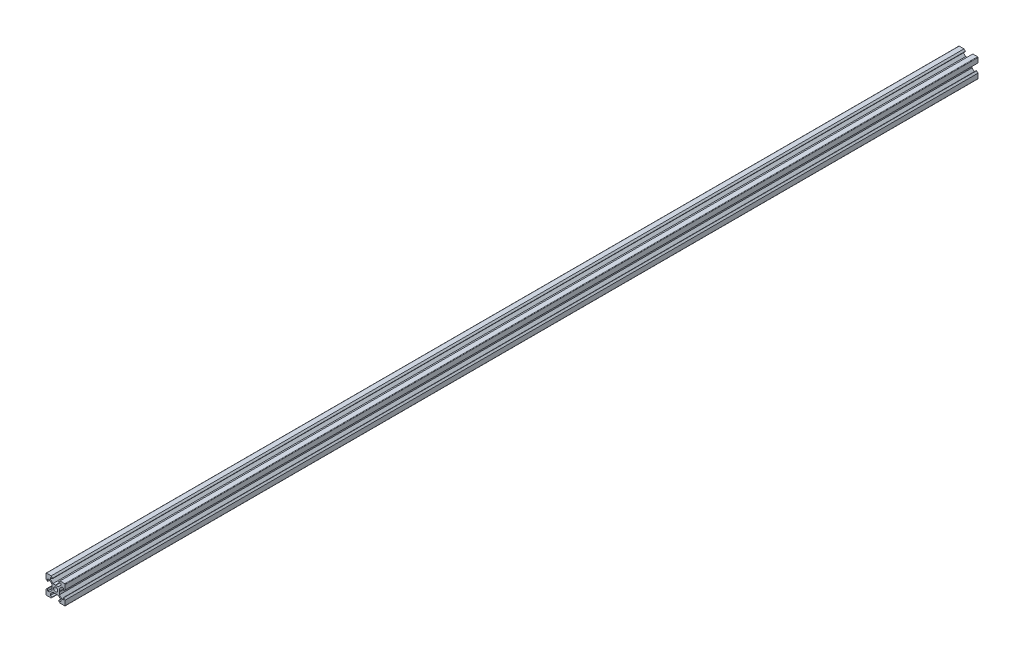
SolidWorks part; units mm, degrees
material "6061-T6 (SS)"
ref_plane "Front Plane" through (0, 0, 0) normal (0, 0, 1) x (1, 0, 0)
ref_plane "Top Plane" through (0, 0, 0) normal (0, 1, 0) x (1, 0, 0)
ref_plane "Right Plane" through (0, 0, 0) normal (1, 0, 0) x (0, 0, -1)
sketch "Sketch1" plane through (0, 0, 0) normal (0, 0, 1) x (1, 0, 0)
  line L1 (9.5, -10) -> (-9.5, -10)
  line L2 (10, -9.5) -> (10, 9.5)
  line L3 (9.5, 10) -> (-9.5, 10)
  line L4 (-10, -9.5) -> (-10, 9.5)
  line L5 (10, -10) -> (-10, 10) construction
  line L6 (10, 10) -> (-10, -10) construction
  circle A0 centre (0, 0) radius 2.1
  arc A1 (-9.5, 10) -> (-10, 9.5) centre (-9.5, 9.5) ccw
  arc A2 (10, 9.5) -> (9.5, 10) centre (9.5, 9.5) ccw
  arc A3 (9.5, -10) -> (10, -9.5) centre (9.5, -9.5) ccw
  arc A4 (-9.5, -10) -> (-10, -9.5) centre (-9.5, -9.5) cw
  point P0 (0, 0)
  line B0 (0, 0) -> (0, 10) construction
  line B1 (0, 3.69) -> (-0.21, 3.9)
  line B2 (-0.21, 3.9) -> (-2.8393, 3.9)
  line B3 (-2.8393, 3.9) -> (-5.5, 6.5607)
  line B4 (-5.5, 6.5607) -> (-5.5, 8.2)
  line B5 (-5.5, 8.2) -> (-3.125, 8.2)
  line B6 (-3.125, 8.2) -> (-3.125, 8.545)
  line B7 (-3.125, 8.545) -> (-4.58, 10)
  line B8 (-4.58, 10) -> (4.58, 10)
  line B9 (0, 0) -> (-5.9132, 5.9132) construction
  line B10 (3.125, 8.545) -> (4.58, 10)
  line B11 (3.125, 8.2) -> (3.125, 8.545)
  line B12 (5.5, 8.2) -> (3.125, 8.2)
  line B13 (5.5, 6.5607) -> (5.5, 8.2)
  line B14 (2.8393, 3.9) -> (5.5, 6.5607)
  line B15 (0.21, 3.9) -> (2.8393, 3.9)
  line B16 (0, 3.69) -> (0.21, 3.9)
  line B17 (0, 0) -> (-10, 0) construction
  line B18 (-3.69, 0) -> (-3.9, -0.21)
  line B19 (-3.9, -0.21) -> (-3.9, -2.8393)
  line B20 (-3.9, -2.8393) -> (-6.5607, -5.5)
  line B21 (-6.5607, -5.5) -> (-8.2, -5.5)
  line B22 (-8.2, -5.5) -> (-8.2, -3.125)
  line B23 (-8.2, -3.125) -> (-8.545, -3.125)
  line B24 (-8.545, -3.125) -> (-10, -4.58)
  line B25 (-10, -4.58) -> (-10, 4.58)
  line B26 (0, 0) -> (-5.9132, -5.9132) construction
  line B27 (-8.545, 3.125) -> (-10, 4.58)
  line B28 (-8.2, 3.125) -> (-8.545, 3.125)
  line B29 (-8.2, 5.5) -> (-8.2, 3.125)
  line B30 (-6.5607, 5.5) -> (-8.2, 5.5)
  line B31 (-3.9, 2.8393) -> (-6.5607, 5.5)
  line B32 (-3.9, 0.21) -> (-3.9, 2.8393)
  line B33 (-3.69, 0) -> (-3.9, 0.21)
  line B34 (0, 0) -> (0, -10) construction
  line B35 (0, -3.69) -> (0.21, -3.9)
  line B36 (0.21, -3.9) -> (2.8393, -3.9)
  line B37 (2.8393, -3.9) -> (5.5, -6.5607)
  line B38 (5.5, -6.5607) -> (5.5, -8.2)
  line B39 (5.5, -8.2) -> (3.125, -8.2)
  line B40 (3.125, -8.2) -> (3.125, -8.545)
  line B41 (3.125, -8.545) -> (4.58, -10)
  line B42 (4.58, -10) -> (-4.58, -10)
  line B43 (0, 0) -> (5.9132, -5.9132) construction
  line B44 (-3.125, -8.545) -> (-4.58, -10)
  line B45 (-3.125, -8.2) -> (-3.125, -8.545)
  line B46 (-5.5, -8.2) -> (-3.125, -8.2)
  line B47 (-5.5, -6.5607) -> (-5.5, -8.2)
  line B48 (-2.8393, -3.9) -> (-5.5, -6.5607)
  line B49 (-0.21, -3.9) -> (-2.8393, -3.9)
  line B50 (0, -3.69) -> (-0.21, -3.9)
  line B51 (0, 0) -> (10, 0) construction
  line B52 (3.69, 0) -> (3.9, 0.21)
  line B53 (3.9, 0.21) -> (3.9, 2.8393)
  line B54 (3.9, 2.8393) -> (6.5607, 5.5)
  line B55 (6.5607, 5.5) -> (8.2, 5.5)
  line B56 (8.2, 5.5) -> (8.2, 3.125)
  line B57 (8.2, 3.125) -> (8.545, 3.125)
  line B58 (8.545, 3.125) -> (10, 4.58)
  line B59 (10, 4.58) -> (10, -4.58)
  line B60 (0, 0) -> (5.9132, 5.9132) construction
  line B61 (8.545, -3.125) -> (10, -4.58)
  line B62 (8.2, -3.125) -> (8.545, -3.125)
  line B63 (8.2, -5.5) -> (8.2, -3.125)
  line B64 (6.5607, -5.5) -> (8.2, -5.5)
  line B65 (3.9, -2.8393) -> (6.5607, -5.5)
  line B66 (3.9, -0.21) -> (3.9, -2.8393)
  line B67 (3.69, 0) -> (3.9, -0.21)
  dimension "D1" = 4.2
  dimension "D3" = 0.5
  dimension "D2" = 20
sketch_block_instance "V Slot 1-4"
sketch_block "V Slot 1" parameters "D1"=10, "D2"=11, "D3"=4.3, "D4"=1.8, "D5"=0.21, "D6"=45, "D7"=9.16, "D8"=1.5, "D9"=6.25
sketch_block_instance "V Slot 1-5"
sketch_block_instance "V Slot 1-6"
sketch_block_instance "V Slot 1-7"
extrude "Boss-Extrude1" add sketch "Sketch1" along normal blind 948.5 contours B67 B52 B53 B54 B55 B56 B57 B58 L2 A2 L3 B10 B11 B12 B13 B14 B15 B16 B1 B2 B3 B4 B5 B6 B7 A1 L4 B27 B28 B29 B30 B31 B32 B33 B18 B19 B20 B21 B22 B23 B24 A4 L1 B44 B45 B46 B47 B48 B49
